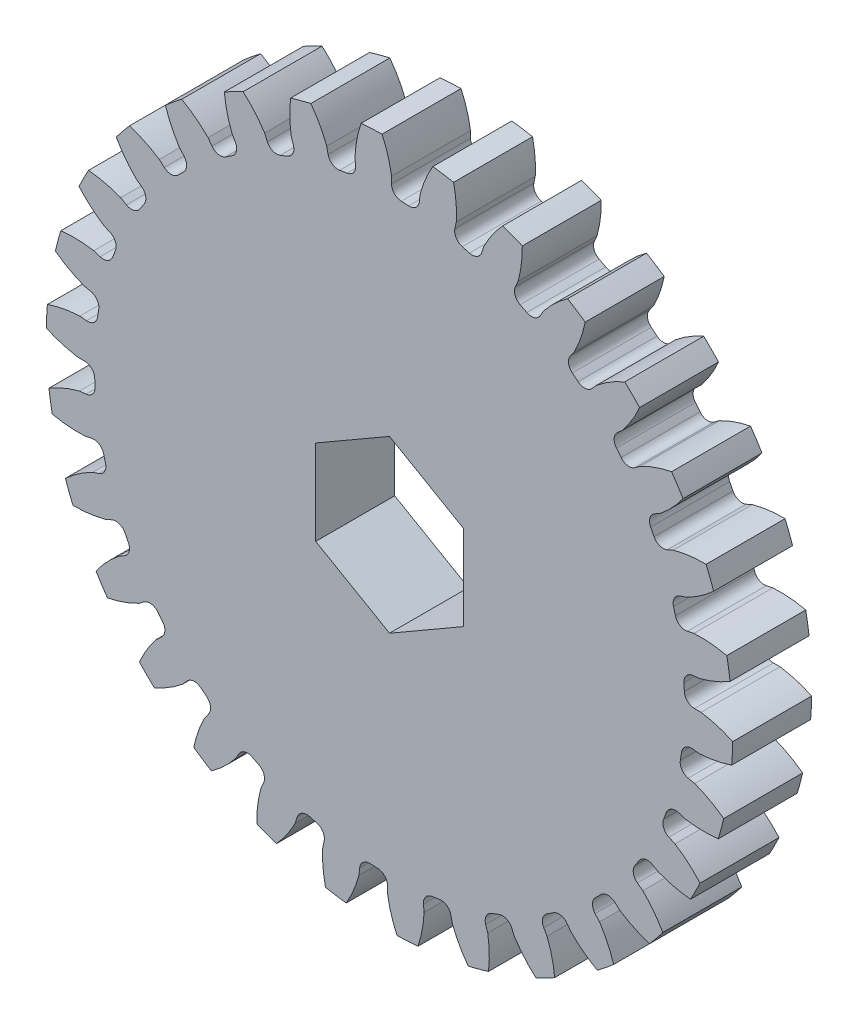
SolidWorks part; units mm, degrees
ref_plane "Front" through (0, 0, 0) normal (0, 0, 1) x (1, 0, 0)
ref_plane "Top" through (0, 0, 0) normal (0, 1, 0) x (1, 0, 0)
ref_plane "Right" through (0, 0, 0) normal (1, 0, 0) x (0, 0, -1)
sketch "Sketch1" plane through (0, 0, 0) normal (0, 0, 1) x (1, 0, 0)
  line L0 (-381, 0) -> (381, 0) construction
  circle A0 centre (0, 0) radius 25.4
  circle A1 centre (0, 0) radius 23.8125 construction
  circle A3 centre (0, 0) radius 21.8281 construction
  dimension "D3" = 1.5875
  dimension "D1" = 3.5719
extrude "Boss-Extrude1" add sketch "Sketch1" against normal blind 5.842
sketch "Sketch2" plane through (0, 0, 0) normal (1, 0, 0) x (0, 0, -1)
  line L0 (12.7, 0) -> (25.4, 0)
  line L1 (12.7, 0) -> (12.7, 20.6375)
  line L2 (12.7, 20.6375) -> (25.4, 20.6375)
  line L3 (25.4, 20.6375) -> (25.4, 0)
  point P5 (25.4, -20.6375)
  point P6 (0, -25.4)
  point P7 (5.842, -25.4)
  point P9 (0, 25.4)
sketch "Sketch3" plane through (0, 0, 0) normal (0, 0, 1) x (1, 0, 0)
  line L0 (0, 0) -> (0, 25.4) construction
  line L1 (-5.7723, 22.3197) -> (0, 23.8125)
  line L2 (-9.5921, 23.8125) -> (9.5921, 23.8125) construction
  line L3 (-9.2865, 21.4108) -> (9.2865, 26.2142) construction
  line L4 (-5.7723, 22.3197) -> (0, 0) construction
  line L5 (-14.7231, 17.7403) -> (0, 0) construction
  line L6 (-14.7231, 17.7403) -> (-2.3552, 28.0047) construction
  line L7 (-4.025, 22.6999) -> (0, 0) construction
  line L8 (-4.025, 22.6999) -> (0.0845, 23.4286) construction
  arc A0 (-5.7723, 22.3197) -> (-14.7231, 17.7403) centre (0, 0) ccw
  circle A1 centre (0, 0) radius 23.8125 construction
  circle A2 centre (0, 0) radius 23.054 construction
  arc A3 (-5.7723, 22.3197) -> (-4.025, 22.6999) centre (0, 0) cw
  circle A4 centre (0, 0) radius 25.4 construction
  point P6 (0, 23.8125)
  dimension "D1" = 5.9622
  dimension "D3" = 16.0725
  dimension "D5" = 4.1735
  dimension "D2" = 10.1357
  dimension "D4" = 1.7887
sketch "Sketch4" plane through (0, 0, 0) normal (0, 0, 1) x (1, 0, 0)
  line L0 (0, 0) -> (1.2445, 23.7473) construction
  line L1 (0.1499, 23.0535) -> (0.1499, 21.8276)
  line L2 (0, 23.8125) -> (2.4891, 23.6821) construction
  line L3 (2.2606, 22.9429) -> (2.1325, 21.7237)
  line L4 (0.1499, 21.8276) -> (0, 0) construction
  line L5 (0, 0) -> (0, 25.4) construction
  line L6 (-14.7231, 17.7403) -> (-2.3552, 28.0047) construction
  line L7 (-14.7231, 17.7403) -> (-2.3552, 28.0047) construction
  arc A0 (2.1325, 21.7237) -> (0.1499, 21.8276) centre (0, 0) ccw
  arc A1 (0, 23.8125) -> (2.4891, 23.6821) centre (0, 0) cw construction
  circle A2 centre (0, 0) radius 23.8125 construction
  circle A3 centre (0, 0) radius 23.054 construction
  circle A4 centre (0, 0) radius 21.8281 construction
  arc A5 (5.2696, 27.6051) -> (-2.3552, 28.0047) centre (0, 0) ccw
  spline S0 degree 2 poles (-2.3552, 28.0047) (-0.2719, 25.8149) (0.1499, 23.0535) knots 0 0 0 1 1 1
  spline S1 degree 2 poles (5.2696, 27.6051) (2.9688, 25.6451) (2.2606, 22.9429) knots 0 0 0 1 1 1
  dimension "D1" = 2.4936
extrude "Cut-Extrude1" cut sketch "Sketch4" against normal through all
fillet "Fillet1" radius 0.7481 2 edges at (2.1325, 21.7237, -2.921) (0.1499, 21.8276, -2.921)
pattern_circular "CirPattern1" count 30 over 360 about axis through (0, 0, -5.842) along (0, 0, 1) of "Cut-Extrude1", "Fillet1"
sketch "Pitch Dia" plane through (0, 0, 0) normal (0, 0, 1) x (1, 0, 0)
  circle A0 centre (0, 0) radius 23.8125 construction
  circle A1 centre (0, 0) radius 23.8125 construction
sketch "Sketch5" plane through (0, 0, 0) normal (0, 0, 1) x (1, 0, 0)
  line L1 (0, 6.3058) -> (-5.461, 3.1529)
  line L2 (-5.461, 3.1529) -> (-5.461, -3.1529)
  line L3 (-5.461, -3.1529) -> (0, -6.3058)
  line L4 (0, -6.3058) -> (5.461, -3.1529)
  line L5 (5.461, -3.1529) -> (5.461, 3.1529)
  line L6 (5.461, 3.1529) -> (0, 6.3058)
  circle A0 centre (0, 0) radius 5.461 construction
  dimension "D1" = 10.922
extrude "Cut-Extrude2" cut sketch "Sketch5" against normal through all both and the other way through all
equation "\"D2@Sketch3\" = \"D1@Sketch3\"*1.7"
equation "\"D3@Sketch3\" = \"D1@Sketch3\"+\"D2@Sketch3\"-.001"
equation "\"D4@Sketch3\" = \"D1@Sketch3\"*.3"
equation "\"D5@Sketch3\" = \"D1@Sketch3\"-\"D4@Sketch3\""
equation "\"D1@Sketch4\" = 1.5708/(\"Number of Teeth@Sketch1\"/\"Ptich Dia@Sketch1\")"
equation "\"D1@Chamfer1\" = \"B Hub Dia@Sketch2\"*.025"
equation "\"D1@CirPattern1\" = \"Number of Teeth@Sketch1\""
equation "\"D1@Fillet1\" = \"D1@Sketch4\"*.3"
equation "\"D1@Fillet2\" = \"OD@Sketch1\"*.01"
equation "\"D1@Sketch1\" = 2.250/(\"Number of Teeth@Sketch1\"/\"Ptich Dia@Sketch1\")"
equation "\"D1@Sketch10\" = \"Set Screw Major Dia.@Sketch8\"*1.08"
equation "\"D2@Sketch11\" = \"D4@Helix/Spiral1\"*.125"
equation "\"D3@Sketch11\" = \"D4@Helix/Spiral1\"*.5"
equation "\"D1@Sketch12\" = \"Set Screw Major Dia.@Sketch8\""
equation "\"D1@Chamfer3\" = \"Set Screw Major Dia.@Sketch8\"*.08"
equation "\"D2@Sketch15\" = \"D4@Helix/Spiral1\"*.125"
equation "\"D3@Sketch15\" = \"D4@Helix/Spiral1\"*.5"
equation "\"D4@Helix/Spiral2\" = \"D4@Helix/Spiral1\""
equation "\"D3@Helix/Spiral1\" = \"D1@Sketch8\""
equation "\"D3@Helix/Spiral2\" = \"D4@Helix/Spiral2\"+\"Screw Lg.@Sketch12\""
